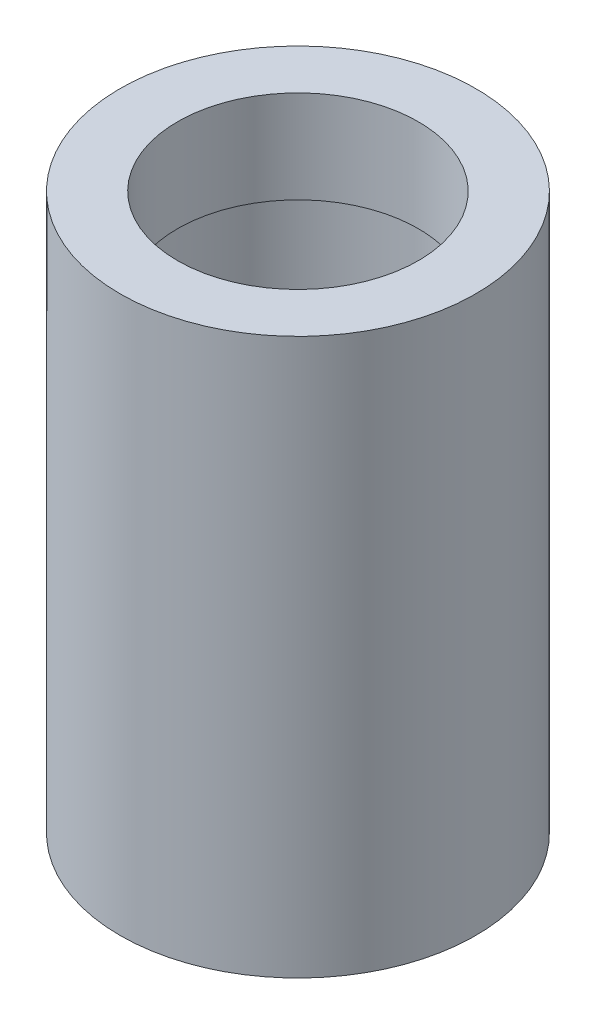
SolidWorks part; units mm, degrees
ref_plane "Alzado" through (0, 0, 0) normal (0, 0, 1) x (1, 0, 0)
ref_plane "Planta" through (0, 0, 0) normal (0, 1, 0) x (1, 0, 0)
ref_plane "Vista lateral" through (0, 0, 0) normal (1, 0, 0) x (0, 0, -1)
sketch "Croquis1" plane through (0, 0, 0) normal (0, 1, 0) x (1, 0, 0)
  circle A0 centre (0, 0) radius 3.5
  circle A1 centre (0, 0) radius 4.8
  dimension "D1" = 7
  dimension "D2" = 9.6
extrude "Saliente-Extruir1" add sketch "Croquis1" along normal blind 15
sketch "Croquis2" plane through (0, 15, 0) normal (0, 1, 0) x (1, 0, 0)
  circle A0 centre (0, 0) radius 3.8662
  circle A1 centre (0, 0) radius 3.25
  dimension "D1" = 6.5
extrude "Saliente-Extruir2" add sketch "Croquis2" against normal blind 2.5
fillet "Redondeo1" radius 0.3 1 edges at (0, 0, 3.5)
